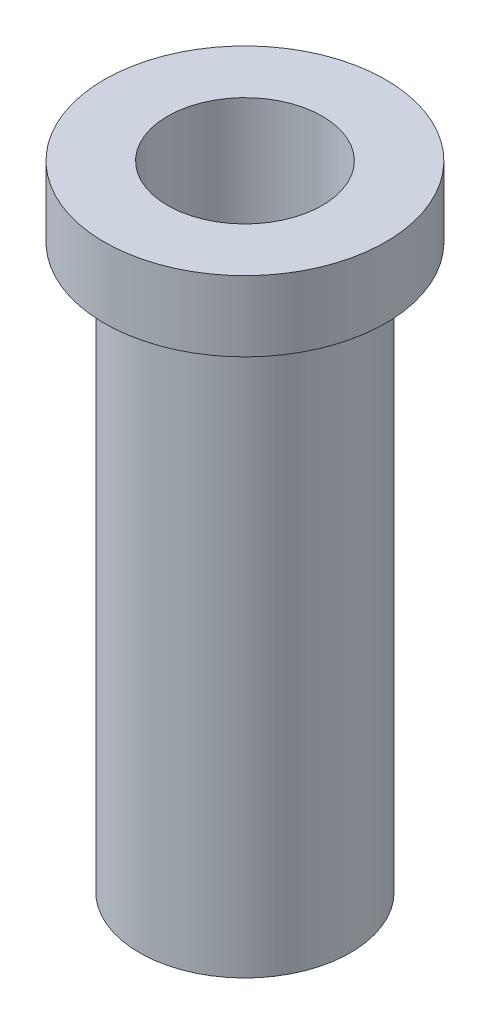
SolidWorks part; units mm, degrees
ref_plane "Front Plane" through (0, 0, 0) normal (0, 0, 1) x (1, 0, 0)
ref_plane "Top Plane" through (0, 0, 0) normal (0, 1, 0) x (1, 0, 0)
ref_plane "Right Plane" through (0, 0, 0) normal (1, 0, 0) x (0, 0, -1)
sketch "Sketch1" plane through (0, 0, 0) normal (0, 0, 1) x (1, 0, 0)
  line L0 (0, 21.5666) -> (0, -23.4334) construction
  line L1 (5.5, 21.5666) -> (5.5, -23.4334)
  line L2 (5.5, -23.4334) -> (7.5, -23.4334)
  line L3 (7.5, -23.4334) -> (7.5, 16.5666)
  line L4 (7.5, 16.5666) -> (10, 16.5666)
  line L5 (10, 16.5666) -> (10, 21.5666)
  line L6 (10, 21.5666) -> (5.5, 21.5666)
  point P9 (7.5, -3.4334)
  dimension "D1" = 5.5
  dimension "D2" = 7.5
  dimension "D3" = 10
  dimension "D4" = 5
  dimension "D5" = 20
  dimension "D6" = 40
revolve "Revolve1" add sketch "Sketch1" angle 360 about L0
